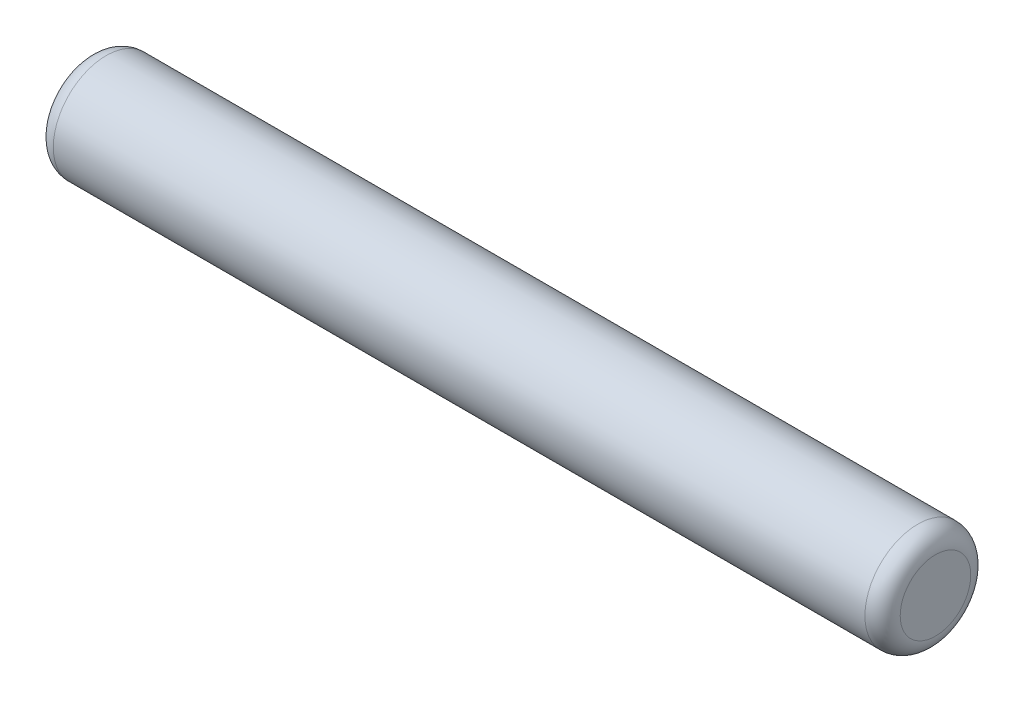
SolidWorks part; units mm, degrees
material "AISI 1015 Steel, Cold Drawn (SS)"
ref_plane "Front" through (0, 0, 0) normal (0, 0, 1) x (1, 0, 0)
ref_plane "Top" through (0, 0, 0) normal (0, 1, 0) x (1, 0, 0)
ref_plane "Right" through (0, 0, 0) normal (1, 0, 0) x (0, 0, -1)
sketch "Sketch1" plane through (0, 0, 0) normal (0, 0, 1) x (1, 0, 0)
  line L0 (-7.3604, 0) -> (82.3299, 0) construction
  line L1 (0, 0) -> (0, 3.175)
  line L2 (1.5875, 4.7625) -> (74.6125, 4.7625)
  line L3 (76.2, 3.175) -> (76.2, 0)
  line L4 (76.2, 0) -> (0, 0)
  arc A0 (0, 3.175) -> (1.5875, 4.7625) centre (1.5875, 3.175) cw
  arc A1 (74.6125, 4.7625) -> (76.2, 3.175) centre (74.6125, 3.175) cw
  dimension "D1" = 9.525
  dimension "D2" = 1.5875
  dimension "D3" = 76.2
revolve "Revolve1" add sketch "Sketch1" angle 360 about L0
ref_plane "Plane1" through (38.1, 0, 0) normal (-1, 0, 0) x (0, 0, 1)
